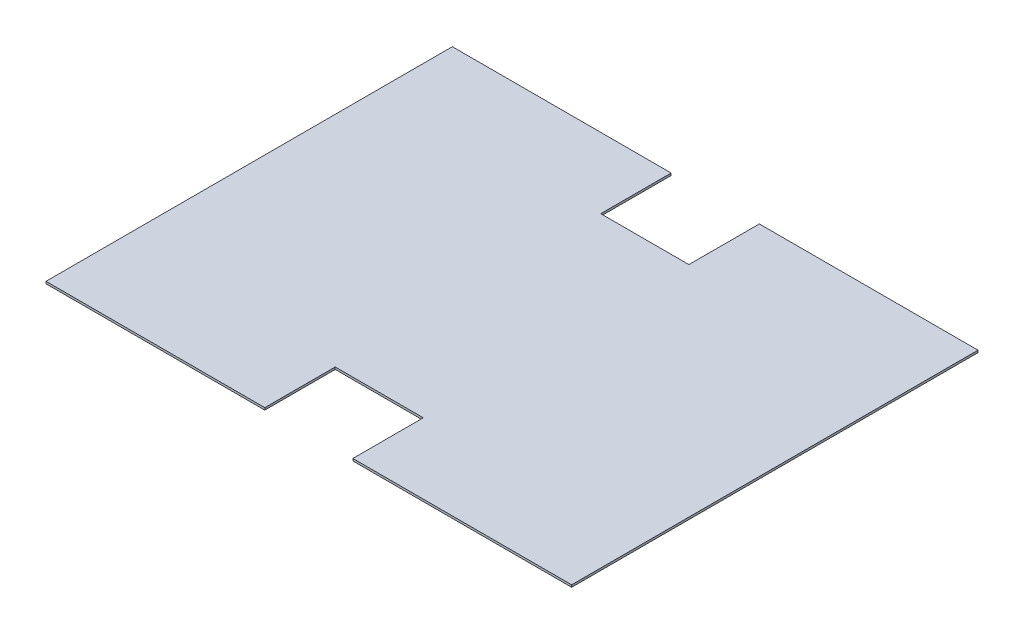
SolidWorks part; units mm, degrees
ref_plane "Front Plane" through (0, 0, 0) normal (0, 0, 1) x (1, 0, 0)
ref_plane "Top Plane" through (0, 0, 0) normal (0, 1, 0) x (1, 0, 0)
ref_plane "Right Plane" through (0, 0, 0) normal (1, 0, 0) x (0, 0, -1)
sketch "Sketch1" plane through (0, 0, 0) normal (0, 1, 0) x (1, 0, 0)
  line L1 (379.095, -293.0525) -> (-379.095, -293.0525)
  line L2 (379.095, -293.0525) -> (379.095, 293.0525)
  line L3 (379.095, 293.0525) -> (-379.095, 293.0525)
  line L4 (-379.095, -293.0525) -> (-379.095, 293.0525)
  line L5 (379.095, -293.0525) -> (-379.095, 293.0525) construction
  line L6 (379.095, 293.0525) -> (-379.095, -293.0525) construction
  point P0 (0, 0)
  dimension "D1" = 586.105
  dimension "D2" = 758.19
extrude "Boss-Extrude1" add sketch "Sketch1" along normal blind 3.175
sketch "Sketch2" plane through (0, 3.175, 0) normal (0, 1, 0) x (1, 0, 0)
  line L0 (0, 293.0525) -> (0, -293.0525) construction
  line L1 (379.095, 293.0525) -> (-379.095, 293.0525) construction
  line L2 (-379.095, -293.0525) -> (379.095, -293.0525) construction
  line L3 (63.5, -293.0525) -> (63.5, -191.4525)
  line L4 (63.5, -293.0525) -> (-63.5, -293.0525)
  line L5 (63.5, -191.4525) -> (-63.5, -191.4525)
  line L6 (-63.5, -293.0525) -> (-63.5, -191.4525)
  line L7 (-63.5, 293.0525) -> (-63.5, 191.4525)
  line L10 (-63.5, 293.0525) -> (63.6782, 293.0525)
  line L11 (-63.5, 191.4525) -> (63.6782, 191.4525)
  line L12 (63.6782, 293.0525) -> (63.6782, 191.4525)
  dimension "D1" = 63.5
  dimension "D2" = 127
  dimension "D3" = 101.6
  dimension "D4" = 101.6
extrude "Cut-Extrude1" cut sketch "Sketch2" against normal up to next
